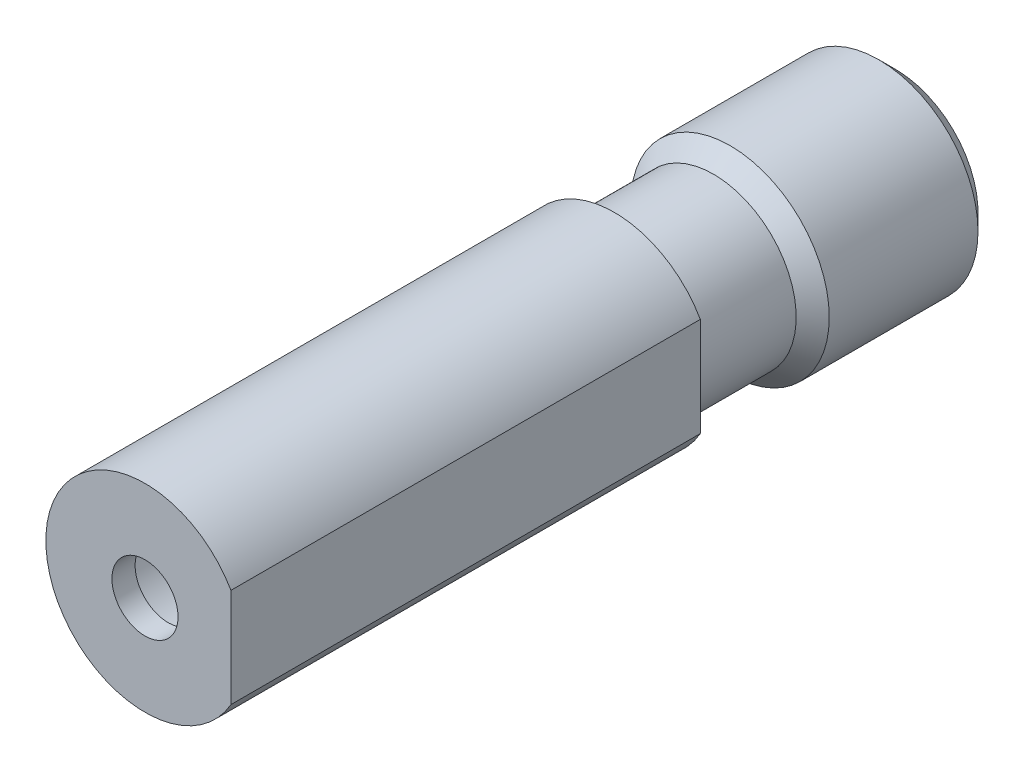
SolidWorks part; units mm, degrees
ref_plane "Спереди" through (0, 0, 0) normal (0, 0, 1) x (1, 0, 0)
ref_plane "Сверху" through (0, 0, 0) normal (0, 1, 0) x (1, 0, 0)
ref_plane "Справа" through (0, 0, 0) normal (1, 0, 0) x (0, 0, -1)
ref_plane "Плоскость1" through (0, 0, 8.5) normal (0, 0, -1) x (-1, 0, 0)
sketch "Эскиз1" plane through (0, 0, 8.5) normal (0, 0, -1) x (-1, 0, 0)
  line L0 (-2.6, 1.4967) -> (-2.6, -1.4967)
  arc A0 (-2.6, -1.4967) -> (-2.6, 1.4967) centre (0, 0) ccw
extrude "Бобышка-Вытянуть1" add sketch "Эскиз1" against normal blind 14.2
ref_plane "Плоскость2" through (0, 0, 0) normal (0, -1, 0) x (1, 0, 0)
sketch "Эскиз2" plane through (0, 0, 0) normal (0, -1, 0) x (1, 0, 0)
  line L0 (2.5, 8.5) -> (0, 8.5)
  line L1 (0, 8.5) -> (0, 0)
  line L2 (0, 0) -> (3, 0)
  line L3 (3, 0) -> (3, 5)
  line L4 (3, 5) -> (2.5, 5.5)
  line L5 (2.5, 5.5) -> (2.5, 8.5)
  line L6 (0, 8.5) -> (0, 0) construction
revolve "Повернуть1" add sketch "Эскиз2" angle 360 about L6
hole_wizard "Цековка для винта с внутренним шестигранником M1.61" positions "Эскиз4" profile "Эскиз3" counterbore size "M1.6" standard "Ansi Metric"
sketch "Эскиз4" plane through (0, 0, 0) normal (0, 0, -1) x (-1, 0, 0)
  point P0 (0, 0)
sketch "Эскиз3" plane through (0, 0, 0) normal (1, 0, 0) x (0, 1, 0)
  line L0 (0, 0) -> (0, 22.7)
  line L1 (0, 22.7) -> (1, 22.7)
  line L3 (1, 22.7) -> (1, 22)
  line L4 (1, 22) -> (2, 22)
  line L5 (2, 22) -> (2, 0)
  line L7 (2, 0) -> (0, 0)
  line L11 (0, -6.35) -> (0, 107.95) construction
  dimension "Диаметр сквозного отверстия" = 2
  dimension "Глубина сквозного отверстия" = 22.7
  dimension "Диаметр цековки" = 4
  dimension "Глубина цековки" = 22
chamfer "Фаска1" distance 0.5 angle 45 1 edges at (-3, 0, 0)
